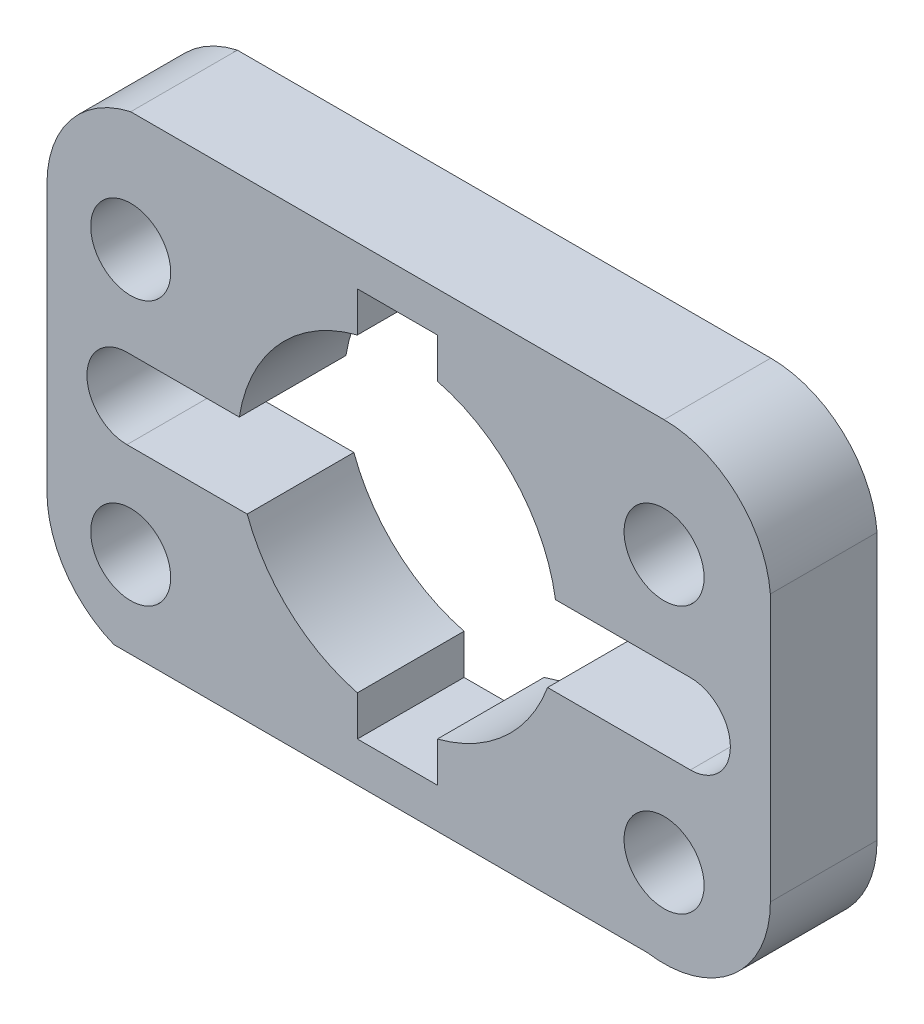
SolidWorks part; units mm, degrees
ref_plane "Front Plane" through (0, 0, 0) normal (0, 0, 1) x (1, 0, 0)
ref_plane "Top Plane" through (0, 0, 0) normal (0, 1, 0) x (1, 0, 0)
ref_plane "Right Plane" through (0, 0, 0) normal (1, 0, 0) x (0, 0, -1)
sketch "Sketch1" plane through (0, 0, 0) normal (0, 0, 1) x (1, 0, 0)
  line L0 (-3.9959, -20.5776) -> (123.0041, -20.5776)
  line L1 (-0.8897, 41.2625) -> (25.8596, 41.2625)
  line L2 (-0.8897, 22.2125) -> (27.7413, 22.2125)
  line L3 (101.1404, 41.2625) -> (133.2616, 41.2625)
  line L4 (99.2587, 22.2125) -> (133.2616, 22.2125)
  line L5 (152.3116, 4.5201) -> (152.3116, 68.0201)
  line L8 (62.3562, 81.7778) -> (53.975, 81.7778)
  line L9 (53.975, 72.2528) -> (53.975, 81.7778)
  line L12 (62.3562, 81.7778) -> (73.025, 81.7778)
  line L13 (73.025, 72.2528) -> (73.025, 81.7778)
  line L16 (62.7996, -11.0526) -> (53.975, -11.0526)
  line L17 (53.975, -1.5276) -> (53.975, -11.0526)
  line L20 (62.7996, -11.0526) -> (73.025, -11.0526)
  line L21 (73.025, -1.5276) -> (73.025, -11.0526)
  line L22 (-19.9397, 2.9966) -> (-19.9397, 66.4966)
  line L23 (0, 91.3028) -> (127, 91.3028)
  circle A0 centre (0, 0) radius 9.525
  circle A1 centre (0.0014, 62.9099) radius 9.525
  circle A2 centre (127.0001, 63.4875) radius 9.525
  circle A3 centre (127, -0.0125) radius 9.525
  arc A4 (27.7413, 22.2125) -> (53.975, -1.5276) centre (63.5, 35.3626) ccw
  arc A5 (-0.8897, 41.2625) -> (-0.8897, 22.2125) centre (-0.8897, 31.7375) ccw
  arc A6 (133.2616, 22.2125) -> (133.2616, 41.2625) centre (133.2616, 31.7375) ccw
  arc A7 (101.1404, 41.2625) -> (73.025, 72.2528) centre (63.5, 35.3626) ccw
  arc A8 (53.975, 72.2528) -> (25.8596, 41.2625) centre (63.5, 35.3626) ccw
  arc A9 (73.025, -1.5276) -> (99.2587, 22.2125) centre (63.5, 35.3626) ccw
  arc A10 (-19.9397, 66.4966) -> (0, 91.3028) centre (5.4603, 66.4966) cw
  arc A11 (127, 91.3028) -> (152.3116, 68.0201) centre (127, 65.9028) cw
  arc A12 (152.3116, 4.5201) -> (123.0041, -20.5776) centre (126.9116, 4.5201) cw
  arc A13 (-19.9397, 2.9966) -> (-3.9959, -20.5776) centre (5.4603, 2.9966) ccw
  point P41 (0, 0)
  dimension "D1" = 19.05
  dimension "D2" = 19.05
  dimension "D3" = 19.05
  dimension "D4" = 19.05
  dimension "D8" = 76.2
  dimension "D10" = 19.05
  dimension "D11" = 19.05
  dimension "D22" = 25.4
  dimension "D23" = 25.4
  dimension "D24" = 25.4
  dimension "D25" = 25.4
  dimension "D26" = 19.05
  dimension "D27" = 19.05
  dimension "D5" = 127
  dimension "D6" = 127
  dimension "D7" = 63.5
  dimension "D9" = 63.5
  dimension "D12" = 31.75
  dimension "D13" = 31.75
  dimension "D14" = 9.525
  dimension "D15" = 9.525
  dimension "D16" = 19.05
  dimension "D17" = 9.525
  dimension "D18" = 9.525
  dimension "D19" = 19.05
  dimension "D20" = 19.05
  dimension "D21" = 19.05
  dimension "D28" = 9.525
  dimension "D29" = 9.525
  dimension "D30" = 127
  dimension "D31" = 127
  dimension "D32" = 63.5
  dimension "D33" = 63.5
extrude "Boss-Extrude1" add sketch "Sketch1" along normal blind 25.4
